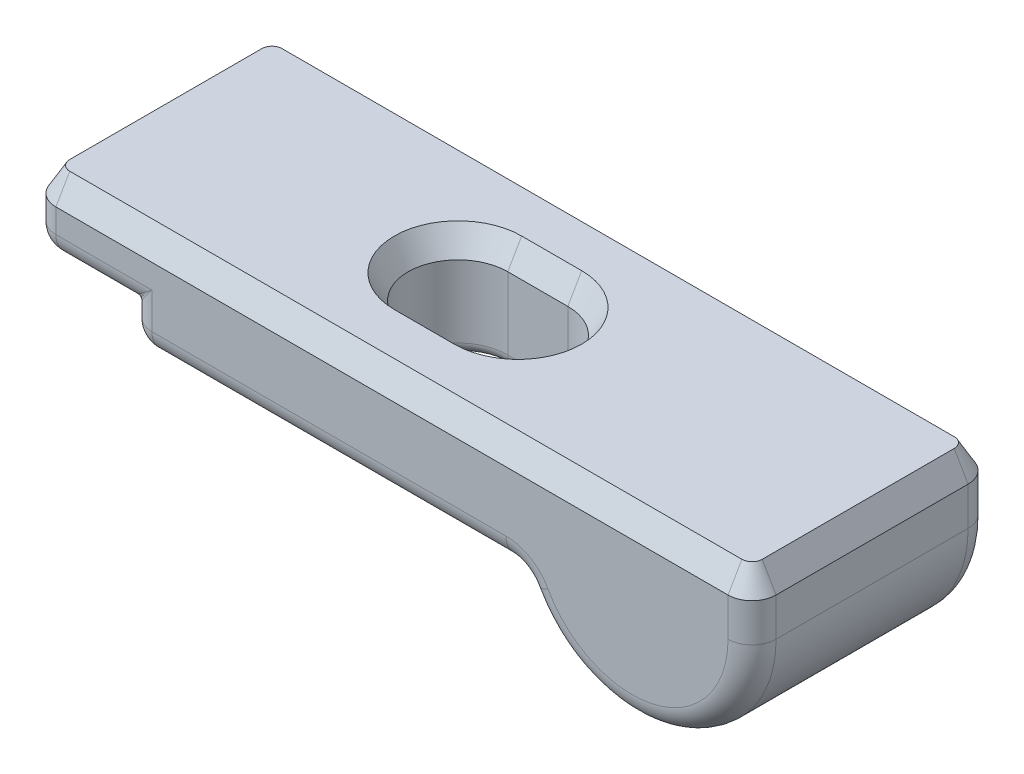
SolidWorks part; units mm, degrees
ref_plane "Front Plane" through (0, 0, 0) normal (0, 0, 1) x (1, 0, 0)
ref_plane "Top Plane" through (0, 0, 0) normal (0, 1, 0) x (1, 0, 0)
ref_plane "Right Plane" through (0, 0, 0) normal (1, 0, 0) x (0, 0, -1)
sketch "Sketch1" plane through (0, 0, 0) normal (0, 0, 1) x (1, 0, 0)
  line L0 (0, 0) -> (8, 0)
  line L1 (8, 0) -> (8, -3)
  line L2 (8, -3) -> (40.7541, -3)
  line L3 (0, 0) -> (0, 6)
  line L4 (0, 6) -> (60, 6)
  line L5 (60, 6) -> (60, 0.8097)
  arc A0 (40.7541, -3) -> (60, 0.8097) centre (50, 0.8097) ccw
  point P3 (0, 0)
  point P9 (51.9418, -9)
  point P10 (41.5917, -2)
  dimension "D5" = 3
  dimension "D6" = 10
  dimension "D1" = 15
  dimension "D2" = 60
  dimension "D3" = 8
  dimension "D4" = 6
extrude "Boss-Extrude1" add sketch "Sketch1" along normal blind 20
sketch "Sketch2" plane through (0, 6, 0) normal (0, 1, 0) x (1, 0, 0)
  line L0 (25.5, -10) -> (30.5, -10) construction
  line L1 (25.5, -5.85) -> (30.5, -5.85)
  line L2 (25.5, -14.15) -> (30.5, -14.15)
  line L3 (60, -20) -> (60, 0) construction
  line L4 (60, -10) -> (0, -10) construction
  line L5 (0, -20) -> (0, 0) construction
  arc A0 (25.5, -5.85) -> (25.5, -14.15) centre (25.5, -10) ccw
  arc A1 (30.5, -14.15) -> (30.5, -5.85) centre (30.5, -10) ccw
  point P2 (28, -10)
  dimension "D1" = 8.3
  dimension "D2" = 5
  dimension "D3" = 28
extrude "Cut-Extrude1" cut sketch "Sketch2" against normal up to next
fillet "Fillet1" radius 2 15 edges at (24.3771, -3, 0) (24.3771, -3, 20) (51.9418, -9, 0) (51.9418, -9, 20) (4, 0, 0) (8, -1.5, 0) (4, 0, 20) (8, -1.5, 20) (40.7541, -3, 10) (60, 3.4048, 0) (60, 3.4048, 20) (0, 3, 0) (0, 3, 20) (8, -3, 10) (0, 0, 10)
chamfer "Chamfer1" distance 2 angle 30 8 edges at (30, 6, 20) (59.4142, 6, 19.4142) (0.5858, 6, 19.4142) (60, 6, 10) (0, 6, 10) (59.4142, 6, 0.5858) (0.5858, 6, 0.5858) (30, 6, 0)
chamfer "Chamfer2" distance 2 angle 30 4 edges at (21.35, 6, 10) (28, 6, 14.15) (28, 6, 5.85) (34.65, 6, 10)
fillet "Fillet2" radius 1 4 edges at (34.65, -3, 10) (28, -3, 5.85) (21.35, -3, 10) (28, -3, 14.15)
fillet "Fillet3" radius 0.5 3 edges at (8.5858, 0.5858, 19.4142) (8.5858, 0.5858, 0.5858) (8, 0, 10)
